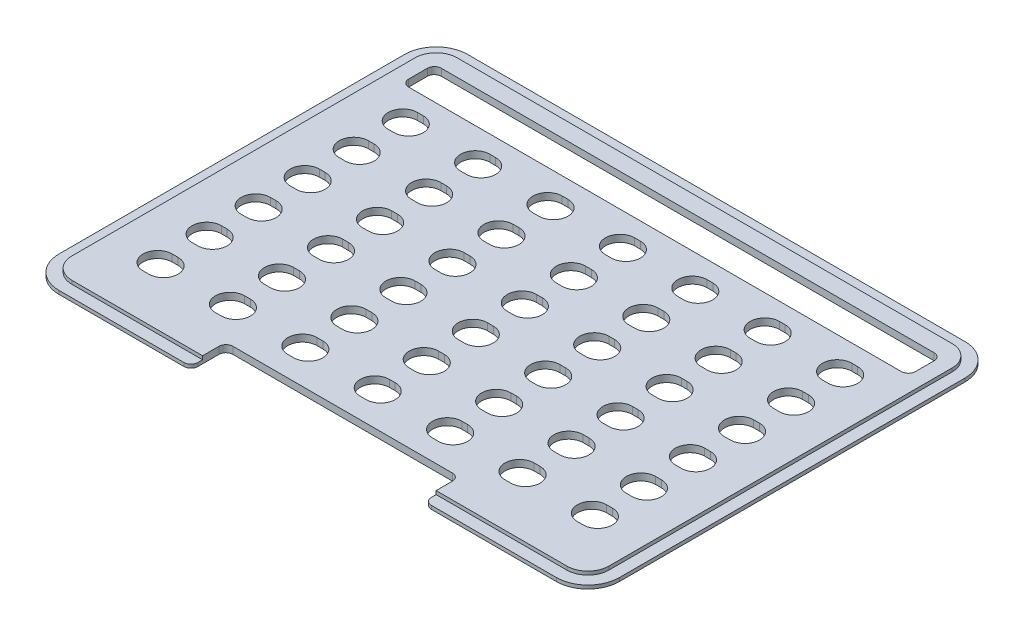
SolidWorks part; units mm, degrees
ref_plane "Front Plane" through (0, 0, 0) normal (0, 0, 1) x (1, 0, 0)
ref_plane "Top Plane" through (0, 0, 0) normal (0, 1, 0) x (1, 0, 0)
ref_plane "Right Plane" through (0, 0, 0) normal (1, 0, 0) x (0, 0, -1)
sketch "Sketch1" plane through (0, 0, 0) normal (0, 1, 0) x (1, 0, 0)
  line L1 (-120, -87.5) -> (120, -87.5)
  line L2 (-120, -87.5) -> (-120, 87.5)
  line L3 (-120, 87.5) -> (120, 87.5)
  line L4 (120, -87.5) -> (120, 87.5)
  line L5 (-120, -87.5) -> (120, 87.5) construction
  line L6 (-120, 87.5) -> (120, -87.5) construction
  point P0 (0, 0)
  dimension "D1" = 240
  dimension "D2" = 175
extrude "Outer Profile" add sketch "Sketch1" along normal blind 1.5
sketch "Sketch2" plane through (0, 1.5, 0) normal (0, 1, 0) x (1, 0, 0)
  line L0 (-120, 87.5) -> (-120, -87.5) construction
  line L1 (-115, -82.5) -> (115, -82.5)
  line L2 (-115, -82.5) -> (-115, 82.5)
  line L3 (-115, 82.5) -> (115, 82.5)
  line L4 (115, -82.5) -> (115, 82.5)
  line L5 (-115, -82.5) -> (115, 82.5) construction
  line L6 (-115, 82.5) -> (115, -82.5) construction
  line L7 (120, 87.5) -> (-120, 87.5) construction
  point P0 (0, 0)
  dimension "D1" = 5
  dimension "D2" = 5
extrude "Inner Profile" add sketch "Sketch2" along normal blind 1.5
fillet "Fillet1" radius 9 4 edges at (115, 2.25, 82.5) (115, 2.25, -82.5) (-115, 2.25, -82.5) (-115, 2.25, 82.5)
fillet "Fillet2" radius 13.5 4 edges at (-120, 0.75, -87.5) (120, 0.75, -87.5) (120, 0.75, 87.5) (-120, 0.75, 87.5)
sketch "Sketch3" plane through (0, 3, 0) normal (0, 1, 0) x (1, 0, 0)
  line L0 (0, 0) -> (0, -50000) construction
  line L1 (-108.5, -67.75) -> (108.5, -67.75) construction
  line L2 (-108.5, -67.75) -> (-108.5, 67.75) construction
  line L3 (-108.5, 67.75) -> (108.5, 67.75) construction
  line L4 (108.5, -67.75) -> (108.5, 67.75) construction
  line L5 (-108.5, -67.75) -> (108.5, 67.75) construction
  line L6 (-108.5, 67.75) -> (108.5, -67.75) construction
  line L7 (-1.25, -57.5) -> (1.25, -57.5) construction
  line L8 (-1.25, -51.25) -> (1.25, -51.25)
  line L9 (-1.25, -63.75) -> (1.25, -63.75)
  line L10 (-106, -82.5) -> (106, -82.5) construction
  arc A0 (-1.25, -51.25) -> (-1.25, -63.75) centre (-1.25, -57.5) ccw
  arc A1 (1.25, -63.75) -> (1.25, -51.25) centre (1.25, -57.5) ccw
  point P0 (0, 0)
  point P5 (0, -57.5)
  point P9 (0, -57.5)
  dimension "D6" = 15
  dimension "D1" = 217
  dimension "D2" = 135.5
  dimension "D3" = 25
  dimension "D5" = 12.5
chamfer "Chamfer" [suppressed] distance 0.5 angle 45
extrude "Cutout" cut sketch "Sketch3" against normal through all
pattern_linear "Cutouts" count 4 spacing 31 along (-1, 0, 0) count 6 spacing 21 along (0, 0, -1) of "Cutout"
mirror "Mirror1" about plane through (0, 0, 0) normal (1, 0, 0) of "Cutouts"
sketch "Sketch4" plane through (0, 3, 0) normal (0, 1, 0) x (1, 0, 0)
  line L0 (0, 82.5) -> (0, 0) construction
  line L1 (-108.5, 61.25) -> (108.5, 61.25)
  line L2 (-108.5, 61.25) -> (-108.5, 75.25)
  line L3 (-108.5, 75.25) -> (108.5, 75.25)
  line L4 (108.5, 61.25) -> (108.5, 75.25)
  line L5 (106, 82.5) -> (-106, 82.5) construction
  line L7 (-108.5, 67.75) -> (108.5, 67.75) construction
  dimension "D1" = 7.5
  dimension "D2" = 14
  dimension "D3" = 217
extrude "Message Window" cut sketch "Sketch4" against normal through all
fillet "Message Window Corners" radius 3 4 edges at (108.5, 1.5, -61.25) (-108.5, 1.5, -61.25) (108.5, 1.5, -75.25) (-108.5, 1.5, -75.25)
sketch "Sketch6" plane through (0, 3, 0) normal (0, 1, 0) x (1, 0, 0)
  line L0 (-106.5, -87.5) -> (106.5, -87.5) construction
  line L1 (-50, -87.5) -> (50, -87.5)
  line L2 (-50, -87.5) -> (-50, -72.5)
  line L3 (-50, -72.5) -> (50, -72.5)
  line L4 (50, -87.5) -> (50, -72.5)
  line L5 (-50, -87.5) -> (50, -72.5) construction
  line L6 (-50, -72.5) -> (50, -87.5) construction
  point P0 (0, -80)
  dimension "D1" = 100
  dimension "D2" = 15
extrude "Base Cutback" cut sketch "Sketch6" against normal through all
fillet "Fillet5" radius 3 4 edges at (-50, 0.75, 87.5) (50, 0.75, 87.5) (50, 1.5, 72.5) (-50, 1.5, 72.5)
chamfer "Edge Chamfer" [suppressed] distance 1 angle 45
